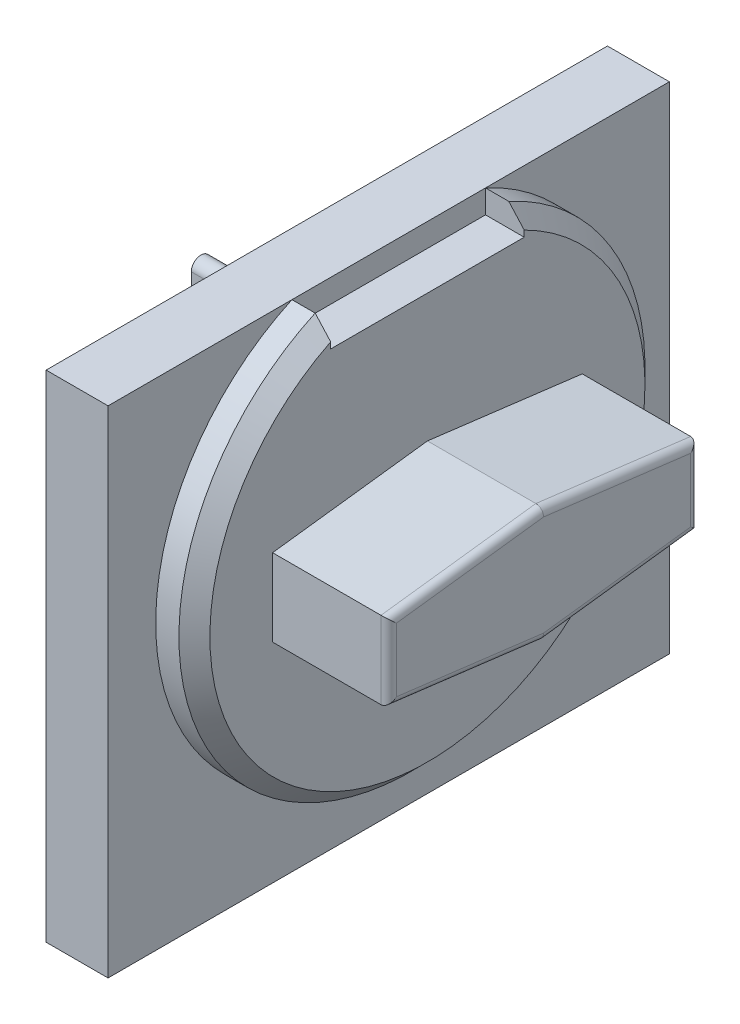
SolidWorks part; units mm, degrees
ref_plane "Front Plane" through (0, 0, 0) normal (0, 0, 1) x (1, 0, 0)
ref_plane "Top Plane" through (0, 0, 0) normal (0, 1, 0) x (1, 0, 0)
ref_plane "Right Plane" through (0, 0, 0) normal (1, 0, 0) x (0, 0, -1)
sketch "Sketch1" plane through (0, 0, 0) normal (1, 0, 0) x (0, 0, -1)
  line L0 (-25.4, -5.936) -> (-25.4, 6.764)
  line L1 (-25.4, 6.764) -> (0, 9.939)
  line L2 (0, 9.939) -> (25.4, 6.764)
  line L3 (25.4, 6.764) -> (25.4, -5.936)
  line L4 (25.4, -5.936) -> (0, -9.111)
  line L5 (0, -9.111) -> (-25.4, -5.936)
  dimension "D1" = 12.7
  dimension "D2" = 19.05
  dimension "D3" = 50.8
extrude "Boss-Extrude1" add sketch "Sketch1" against normal blind 19.05
sketch "Sketch2" plane through (-19.05, 0, 0) normal (-1, 0, 0) x (0, 0, 1)
  circle A0 centre (0, 0) radius 38.2228
extrude "Boss-Extrude2" add sketch "Sketch2" along normal blind 6.35
sketch "Sketch3" plane through (-19.05, 0, 0) normal (1, 0, 0) x (0, 0, -1)
  line L0 (0, 44.2757) -> (0, 30.9426) construction
  line L1 (-15.875, 44.2757) -> (15.875, 44.2757)
  line L2 (-15.875, 44.2757) -> (-15.875, 30.9426)
  line L3 (-15.875, 30.9426) -> (15.875, 30.9426)
  line L4 (15.875, 44.2757) -> (15.875, 30.9426)
  dimension "D1" = 31.75
extrude "Cut-Extrude1" cut sketch "Sketch3" against normal blind 6.35
sketch "Sketch4" plane through (-25.4, 0, 0) normal (-1, 0, 0) x (0, 0, 1)
  line L1 (-46.0375, 34.7702) -> (46.0375, 34.7702)
  line L2 (-46.0375, 34.7702) -> (-46.0375, -46.5098)
  line L3 (-46.0375, -46.5098) -> (46.0375, -46.5098)
  line L4 (46.0375, 34.7702) -> (46.0375, -46.5098)
  point P4 (0, 34.7702)
  dimension "D1" = 81.28
  dimension "D2" = 92.075
extrude "Boss-Extrude3" add sketch "Sketch4" along normal blind 10.16
chamfer "Chamfer1" distance 2.54 angle 45 1 edges at (-19.05, -38.2228, 0)
fillet "Fillet1" radius 1.27 6 edges at (0, 0.414, 25.4) (0, 8.3515, 12.7) (0, 8.3515, -12.7) (0, 0.414, -25.4) (0, -7.5235, -12.7) (0, -7.5235, 12.7)
sketch "Sketch5" plane through (-35.56, 0, 0) normal (-1, 0, 0) x (0, 0, 1)
  circle A0 centre (0, 0) radius 3.175
  dimension "D1" = 6.35
extrude "Boss-Extrude4" add sketch "Sketch5" along normal blind 15.875
sketch "Sketch6" plane through (-51.435, 0, 0) normal (-1, 0, 0) x (0, 0, 1)
  line L0 (11.6244, 11.3837) -> (7.5427, 6.5194)
  line L1 (9.1922, 13.4246) -> (5.1105, 8.5602)
  line L2 (-1.5875, 16.1925) -> (-1.5875, 9.8425)
  line L3 (16.2222, 1.2484) -> (9.9686, 0.1457)
  line L4 (1.5875, 16.1925) -> (1.5875, 9.8425)
  line L5 (15.6708, 4.3752) -> (9.4173, 3.2725)
  line L6 (13.2294, -9.4711) -> (7.7301, -6.2961)
  line L7 (14.8169, -6.7214) -> (9.3176, -3.5464)
  line L8 (4.0464, -15.7589) -> (1.8746, -9.7919)
  line L9 (7.0299, -14.673) -> (4.8581, -8.706)
  line L10 (-7.0299, -14.673) -> (-4.8581, -8.706)
  line L11 (-4.0464, -15.7589) -> (-1.8746, -9.7919)
  line L12 (-14.8169, -6.7214) -> (-9.3176, -3.5464)
  line L13 (-13.2294, -9.4711) -> (-7.7301, -6.2961)
  line L14 (-15.6708, 4.3752) -> (-9.4173, 3.2725)
  line L15 (-16.2222, 1.2484) -> (-9.9686, 0.1457)
  line L16 (-9.1922, 13.4246) -> (-5.1105, 8.5602)
  line L17 (-11.6244, 11.3837) -> (-7.5427, 6.5194)
  circle A0 centre (0, 0) radius 17.78 construction
  arc A1 (-1.5875, 16.1925) -> (1.5875, 16.1925) centre (0, 16.1925) cw
  arc A2 (9.1922, 13.4246) -> (11.6244, 11.3837) centre (10.4083, 12.4042) cw
  arc A3 (15.6708, 4.3752) -> (16.2222, 1.2484) centre (15.9465, 2.8118) cw
  arc A4 (14.8169, -6.7214) -> (13.2294, -9.4711) centre (14.0231, -8.0963) cw
  arc A5 (7.0299, -14.673) -> (4.0464, -15.7589) centre (5.5382, -15.216) cw
  arc A6 (-4.0464, -15.7589) -> (-7.0299, -14.673) centre (-5.5382, -15.216) cw
  arc A7 (-13.2294, -9.4711) -> (-14.8169, -6.7214) centre (-14.0231, -8.0962) cw
  arc A8 (-16.2222, 1.2484) -> (-15.6708, 4.3752) centre (-15.9465, 2.8118) cw
  arc A9 (-11.6244, 11.3837) -> (-9.1922, 13.4246) centre (-10.4083, 12.4042) cw
  arc A10 (1.5875, 9.8425) -> (5.1105, 8.5602) centre (3.5824, 9.8425) ccw
  arc A11 (7.5427, 6.5194) -> (9.4173, 3.2725) centre (9.0709, 5.2371) ccw
  arc A12 (9.9686, 0.1457) -> (9.3176, -3.5464) centre (10.315, -1.8188) ccw
  arc A13 (7.7301, -6.2961) -> (4.8581, -8.706) centre (6.7327, -8.0237) ccw
  arc A14 (1.8746, -9.7919) -> (-1.8746, -9.7919) centre (0, -10.4742) ccw
  arc A15 (-4.8581, -8.706) -> (-7.7301, -6.2961) centre (-6.7327, -8.0237) ccw
  arc A16 (-9.3176, -3.5464) -> (-9.9686, 0.1457) centre (-10.315, -1.8188) ccw
  arc A17 (-9.4173, 3.2725) -> (-7.5427, 6.5194) centre (-9.0709, 5.2371) ccw
  arc A18 (-5.1105, 8.5602) -> (-1.5875, 9.8425) centre (-3.5824, 9.8425) ccw
  dimension "D1" = 35.56
  dimension "D2" = 3.175
  dimension "D3" = 6.35
  dimension "D4" = 9
  dimension "D5" = 9
extrude "Boss-Extrude5" add sketch "Sketch6" along normal blind 4.7625
